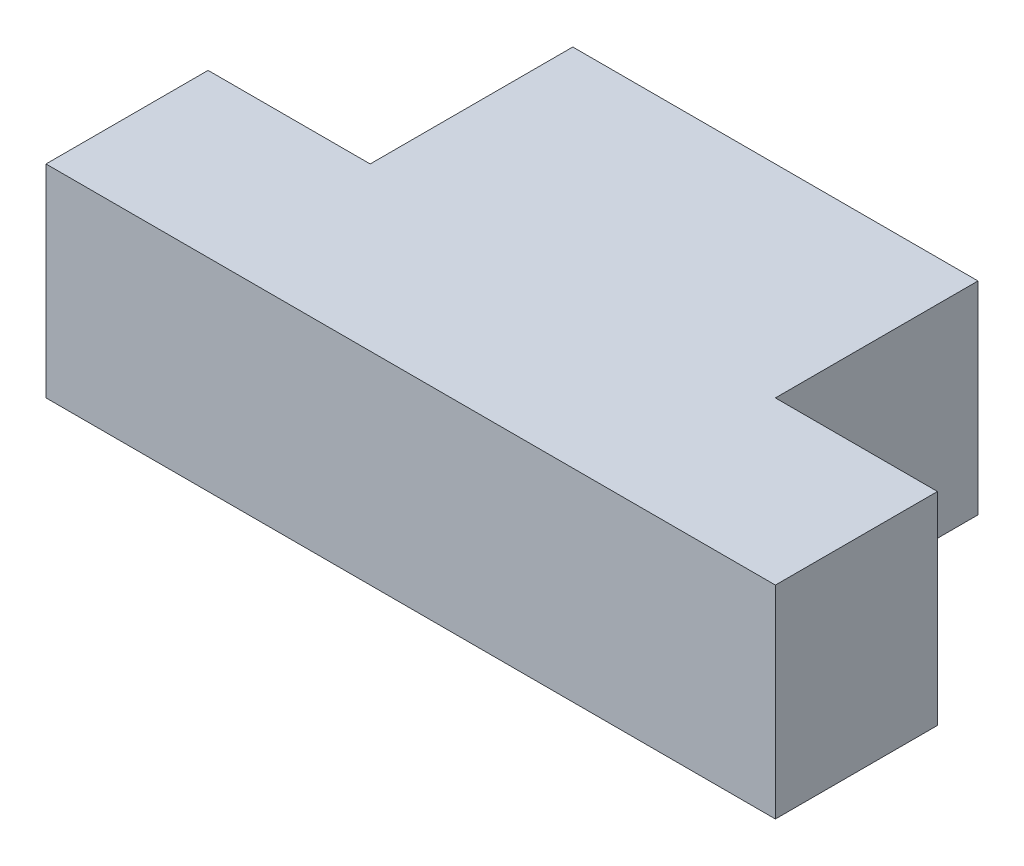
SolidWorks part; units mm, degrees
ref_plane "前视基准面" through (0, 0, 0) normal (0, 0, 1) x (1, 0, 0)
ref_plane "上视基准面" through (0, 0, 0) normal (0, 1, 0) x (1, 0, 0)
ref_plane "右视基准面" through (0, 0, 0) normal (1, 0, 0) x (0, 0, -1)
sketch "草图1" plane through (0, 0, 0) normal (0, 1, 0) x (1, 0, 0)
  line L0 (-3.1587, -1.619) -> (5.8413, -1.619)
  line L1 (5.8413, -1.619) -> (5.8413, 0.381)
  line L2 (5.8413, 0.381) -> (3.8413, 0.381)
  line L3 (3.8413, 0.381) -> (3.8413, 2.881)
  line L4 (3.8413, 2.881) -> (-1.1587, 2.881)
  line L5 (-1.1587, 2.881) -> (-1.1587, 0.381)
  line L6 (-1.1587, 0.381) -> (-3.1587, 0.381)
  line L7 (-3.1587, 0.381) -> (-3.1587, -1.619)
  dimension "D1" = 2
  dimension "D2" = 2.5
  dimension "D3" = 9
  dimension "D4" = 5
extrude "凸台-拉伸1" add sketch "草图1" along normal blind 2.5
